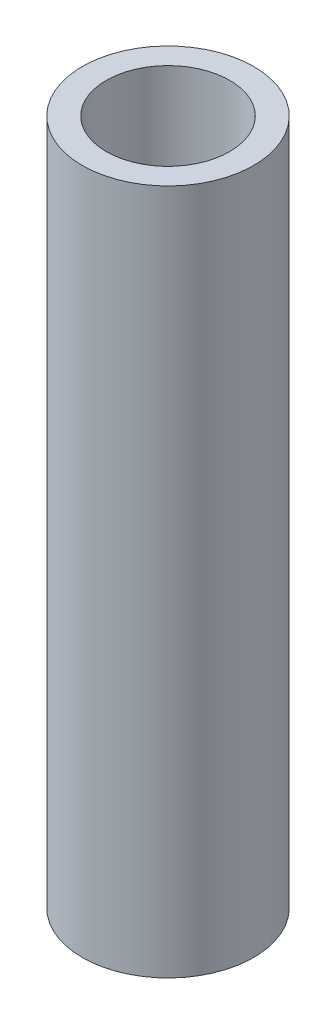
SolidWorks part; units mm, degrees
ref_plane "Front Plane" through (0, 0, 0) normal (0, 0, 1) x (1, 0, 0)
ref_plane "Top Plane" through (0, 0, 0) normal (0, 1, 0) x (1, 0, 0)
ref_plane "Right Plane" through (0, 0, 0) normal (1, 0, 0) x (0, 0, -1)
sketch "Sketch1" plane through (0, 0, 0) normal (0, 1, 0) x (1, 0, 0)
  circle A0 centre (0, 0) radius 2.286
  circle A1 centre (0, 0) radius 3.175
  dimension "D1" = 4.572
  dimension "D2" = 6.35
extrude "Boss-Extrude1" add sketch "Sketch1" along normal blind 25.4
fillet "Fillet2" [suppressed] radius 0.254
